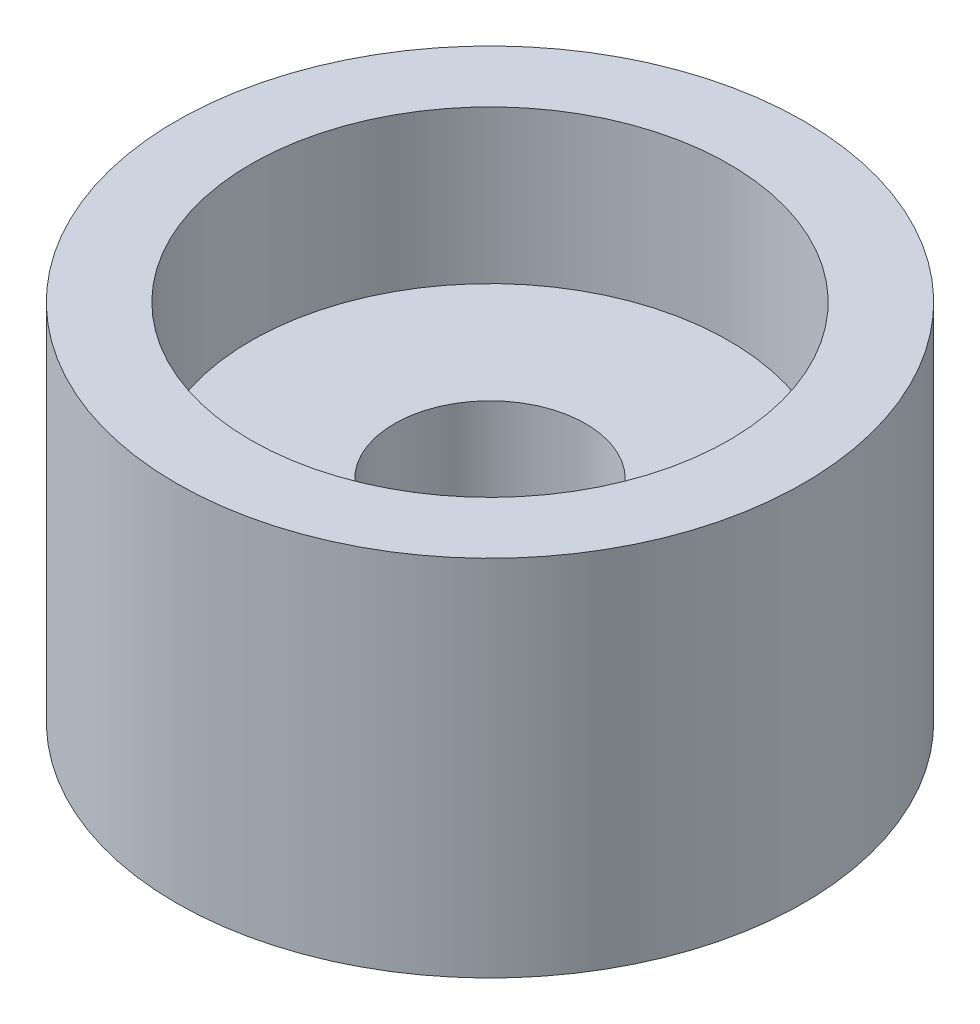
SolidWorks part; units mm, degrees
ref_plane "Front Plane" through (0, 0, 0) normal (0, 0, 1) x (1, 0, 0)
ref_plane "Top Plane" through (0, 0, 0) normal (0, 1, 0) x (1, 0, 0)
ref_plane "Right Plane" through (0, 0, 0) normal (1, 0, 0) x (0, 0, -1)
sketch "Sketch1" plane through (0, 0, 0) normal (0, 1, 0) x (1, 0, 0)
  circle A0 centre (0, 0) radius 8.2
  dimension "D1" = 16.4
extrude "Boss-Extrude1" add sketch "Sketch1" along normal blind 9.5
sketch "Sketch2" plane through (0, 9.5, 0) normal (0, 1, 0) x (1, 0, 0)
  circle A0 centre (0, 0) radius 6.25
  dimension "D1" = 12.5
extrude "Cut-Extrude1" cut sketch "Sketch2" against normal blind 4
sketch "Sketch3" plane through (0, 5.5, 0) normal (0, 1, 0) x (1, 0, 0)
  circle A0 centre (0, 0) radius 2.5
  dimension "D1" = 5
extrude "Cut-Extrude2" cut sketch "Sketch3" against normal through all
